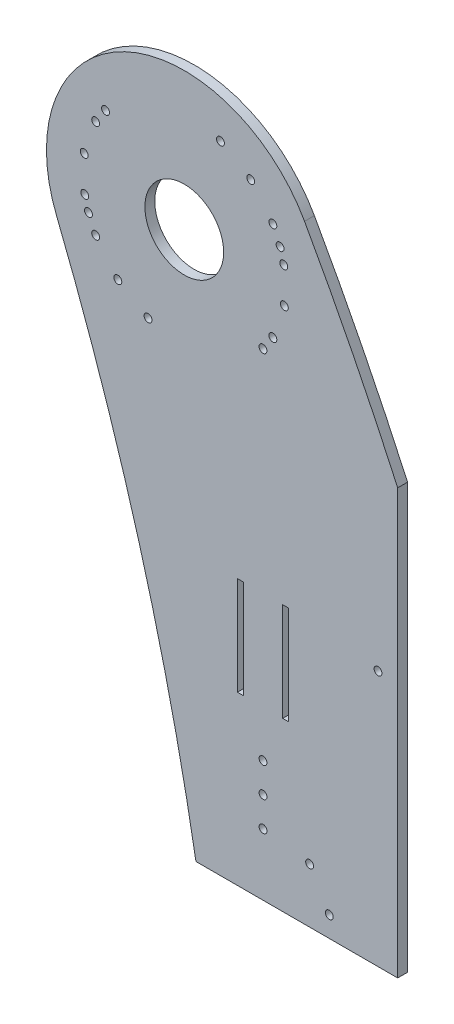
SolidWorks part; units mm, degrees
ref_plane "前视基准面" through (0, 0, 0) normal (0, 0, 1) x (1, 0, 0)
ref_plane "上视基准面" through (0, 0, 0) normal (0, 1, 0) x (1, 0, 0)
ref_plane "右视基准面" through (0, 0, 0) normal (1, 0, 0) x (0, 0, -1)
sketch "草图1" plane through (0, 0, 0) normal (0, 0, 1) x (1, 0, 0)
  line L0 (0, 0) -> (-100, 0) construction
  line L1 (0, 0) -> (100, 0) construction
  line L2 (-100, 0) -> (-100, -10)
  line L3 (-100, -10) -> (100, -10)
  line L4 (100, -10) -> (100, 0)
  line L5 (-91, -10) -> (-91, 11)
  line L6 (-91, 11) -> (-69, 11)
  line L7 (-69, 11) -> (-69, -10)
  line L9 (-93, 460) -> (-90, 460)
  line L10 (-93, 460) -> (-93, 410)
  line L11 (-93, 410) -> (-90, 410)
  line L12 (-90, 460) -> (-90, 410)
  line L13 (-93, 460) -> (-90, 410) construction
  line L14 (-93, 410) -> (-90, 460) construction
  line L15 (-70, 460) -> (-67, 460)
  line L16 (-70, 460) -> (-70, 410)
  line L17 (-70, 410) -> (-67, 410)
  line L18 (-67, 460) -> (-67, 410)
  line L19 (-70, 460) -> (-67, 410) construction
  line L20 (-70, 410) -> (-67, 460) construction
  circle A0 centre (0, 0) radius 2
  circle A1 centre (-120, 600) radius 20
  circle A2 centre (-120, 600) radius 70
  arc A3 (100, 0) -> (-58.9118, 634.1794) centre (-1149.7728, 23.8333) ccw
  arc A4 (-100, 0) -> (-184.9752, 573.9573) centre (-1345.2465, 108.9084) ccw
  circle A5 centre (50, 0) radius 2
  circle A6 centre (-50, 0) radius 2
  point P22 (-91.5, 435)
  point P27 (-68.5, 435)
  dimension "D1" = 4
  dimension "D2" = 40
  dimension "D4" = 120
  dimension "D5" = 140
  dimension "D8" = 2500
  dimension "D9" = 2500
  dimension "D11" = 4
  dimension "D12" = 4
  dimension "D22" = 1
  dimension "D3" = 600
  dimension "D6" = 100
  dimension "D7" = 100
  dimension "D10" = 10
  dimension "D13" = 21
  dimension "D14" = 22
  dimension "D15" = 19
  dimension "D16" = 50
  dimension "D17" = 3
  dimension "D18" = 50
  dimension "D19" = 3
  dimension "D20" = 470
  dimension "D21" = 20
extrude "凸台-拉伸1" add sketch "草图1" along normal blind 5
sketch "草图2" plane through (0, 0, 0) normal (0, 0, -1) x (-1, 0, 0)
  circle A0 centre (80, 386.4102) radius 2 construction
  circle A1 centre (80, 371.4102) radius 2 construction
  circle A2 centre (80, 356.4102) radius 2 construction
  circle A3 centre (56.3397, 352.7499) radius 2 construction
  circle A4 centre (46.3397, 335.4294) radius 2 construction
  circle A5 centre (26.3397, 300.7884) radius 2 construction
  circle A6 centre (6.3397, 266.1474) radius 2 construction
  circle A7 centre (-13.6603, 231.5064) radius 2 construction
  circle A8 centre (80, 76.4102) radius 2 construction
  circle A9 centre (80, 116.4102) radius 2 construction
  circle A10 centre (80, 236.4102) radius 2 construction
  circle A11 centre (80, 276.4102) radius 2 construction
  circle A12 centre (80, 316.4102) radius 2 construction
  circle A13 centre (80, 386.4102) radius 2
  circle A14 centre (80, 371.4102) radius 2
  circle A15 centre (80, 356.4102) radius 2
  circle A16 centre (56.3397, 352.7499) radius 2
  circle A17 centre (46.3397, 335.4294) radius 2
  circle A18 centre (26.3397, 300.7884) radius 2
  circle A19 centre (6.3397, 266.1474) radius 2
  circle A20 centre (-13.6603, 231.5064) radius 2
  circle A21 centre (80, 76.4102) radius 2
  circle A22 centre (80, 116.4102) radius 2
  circle A23 centre (80, 236.4102) radius 2
  circle A24 centre (80, 276.4102) radius 2
  circle A25 centre (80, 316.4102) radius 2
extrude "切除-拉伸1" cut sketch "草图2" against normal through all
sketch "草图3" plane through (0, 0, 5) normal (0, 0, 1) x (1, 0, 0)
  line L0 (-168.6576, 583.194) -> (-120, 600) construction
  line L1 (-165, 625) -> (-75, 625) construction
  line L2 (-165, 625) -> (-165, 575) construction
  line L3 (-165, 575) -> (-75, 575) construction
  line L4 (-75, 625) -> (-75, 575) construction
  line L5 (-165, 625) -> (-75, 575) construction
  line L6 (-165, 575) -> (-75, 625) construction
  line L7 (-86.2643, 638.8832) -> (-120, 600) construction
  circle A0 centre (-165, 625) radius 2
  circle A1 centre (-75, 625) radius 2
  circle A2 centre (-75, 575) radius 2
  circle A3 centre (-165, 575) radius 2
  circle A4 centre (-168.6576, 583.194) radius 2
  circle A5 centre (-159.9751, 632.4344) radius 2
  circle A6 centre (-71.3424, 616.806) radius 2
  circle A7 centre (-80.0249, 567.5656) radius 2
  circle A12 centre (-86.2643, 638.8832) radius 2
  circle A13 centre (-69.1633, 591.8986) radius 2
  circle A14 centre (-153.7357, 561.1168) radius 2
  circle A15 centre (-170.8367, 608.1014) radius 2
  circle A16 centre (-101.5977, 648.0766) radius 2
  circle A17 centre (-69.4583, 609.7743) radius 2
  circle A18 centre (-138.4023, 551.9234) radius 2
  circle A19 centre (-170.5417, 590.2257) radius 2
  point P0 (-120, 600)
  point P29 (-120, 600)
  point P47 (-120, 600)
  dimension "D3" = 4
  dimension "D4" = 4
  dimension "D5" = 4
  dimension "D6" = 4
  dimension "D1" = 50
  dimension "D2" = 90
  dimension "D8" = 10
  dimension "D10" = 20
  dimension "D7" = 2
  dimension "D9" = 3
extrude "切除-拉伸2" cut sketch "草图3" against normal through all
ref_plane "基准面1" through (0, 325, 0) normal (0, -1, 0) x (-1, 0, 0)
split "分割1" trim tools "基准面1" bodies to split 103 resulting bodies 104 105
delete or keep bodies "实体-删除/保留 1" type delete bodies bodies 105
sketch "草图4" plane through (0, 0, 5) normal (0, 0, 1) x (1, 0, 0)
  line L0 (-11.5957, 325) -> (-11.5957, 540.605)
  line L2 (-114.0664, 325) -> (63.4043, 325) construction
  line L3 (-114.0664, 325) -> (63.4043, 325)
  line L4 (-11.5957, 325) -> (63.4043, 325)
  circle A0 centre (-21.5957, 455) radius 2
  arc A3 (-114.0664, 325) -> (-184.9752, 573.9573) centre (-1345.2465, 108.9084) ccw
  arc A4 (63.4043, 325) -> (-58.9118, 634.1794) centre (-1149.7728, 23.8333) ccw
  arc A5 (-58.9118, 634.1794) -> (-184.9752, 573.9573) centre (-120, 600) ccw
  arc A7 (63.4043, 325) -> (-11.5957, 540.605) centre (-1149.7728, 23.8333) ccw
  dimension "D3" = 4
  dimension "D4" = 130
  dimension "D5" = 10
  dimension "D1" = 75
  dimension "D2" = 0
extrude "切除-拉伸3" cut sketch "草图4" against normal blind 10
